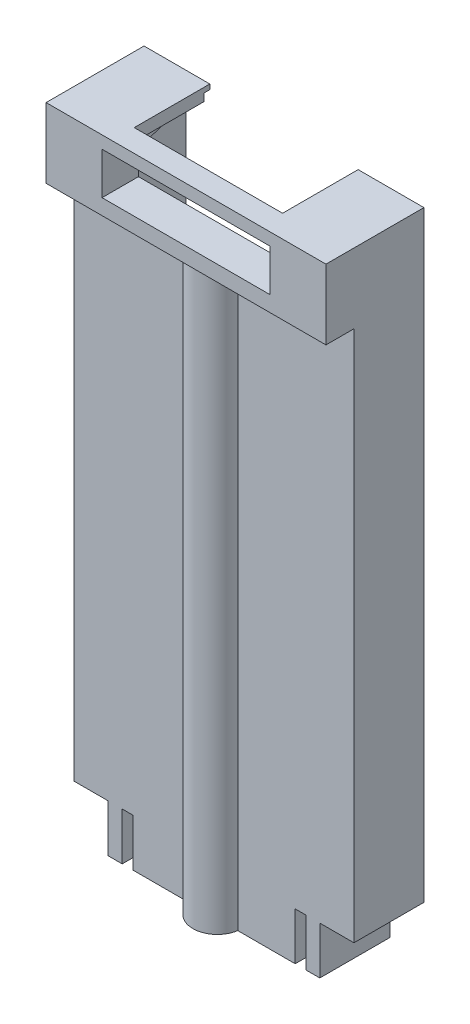
SolidWorks part; units mm, degrees
ref_plane "Front Plane" through (0, 0, 0) normal (0, 0, 1) x (1, 0, 0)
ref_plane "Top Plane" through (0, 0, 0) normal (0, 1, 0) x (1, 0, 0)
ref_plane "Right Plane" through (0, 0, 0) normal (1, 0, 0) x (0, 0, -1)
sketch "Sketch2" plane through (0, 0, 0) normal (0, 0, 1) x (1, 0, 0)
  line L1 (0, 0) -> (20, 0)
  line L2 (0, 0) -> (0, 43)
  line L3 (0, 43) -> (20, 43)
  line L4 (20, 0) -> (20, 43)
  dimension "D1" = 20
  dimension "D2" = 43
extrude "Boss-Extrude1" add sketch "Sketch2" along normal blind 5
sketch "Sketch3" plane through (0, 0, 5) normal (0, 0, 1) x (1, 0, 0)
  line L0 (20, 0) -> (20, 43) construction
  line L1 (0, 43) -> (20, 43)
  line L2 (0, 43) -> (0, 38)
  line L3 (0, 38) -> (20, 38)
  line L4 (20, 43) -> (20, 38)
  dimension "D1" = 5
extrude "Boss-Extrude2" add sketch "Sketch3" along normal blind 2
sketch "Sketch4" plane through (0, 0, 0) normal (0, -1, 0) x (1, 0, 0)
  line L0 (0, 5) -> (20, 5) construction
  line L1 (0, 5) -> (2.44, 5) construction
  line L2 (20, 5) -> (17.56, 5) construction
  line L3 (0, 0) -> (20, 0) construction
  line L4 (2.44, 5) -> (3.44, 5)
  line L5 (2.44, 5) -> (2.44, 0)
  line L6 (2.44, 0) -> (3.44, 0)
  line L7 (3.44, 5) -> (3.44, 0)
  line L8 (20, 5) -> (20, 0) construction
  line L9 (17.56, 5) -> (16.56, 5)
  line L10 (17.56, 5) -> (17.56, 0)
  line L11 (17.56, 0) -> (16.56, 0)
  line L12 (16.56, 5) -> (16.56, 0)
  line L13 (0, 5) -> (0, 0) construction
  dimension "D1" = 1
  dimension "D2" = 1
  dimension "D3" = 2.44
  dimension "D4" = 2.44
extrude "Boss-Extrude4" add sketch "Sketch4" along normal blind 3.4
sketch "Sketch6" plane through (0, 0, 0) normal (0, -1, 0) x (1, 0, 0)
  line L0 (3.44, 5) -> (4.2, 5) construction
  line L1 (3.44, 5) -> (16.56, 5) construction
  line L2 (16.56, 5) -> (15.8, 5) construction
  line L3 (0, 5) -> (20, 5) construction
  line L4 (3.44, 0) -> (16.56, 0) construction
  line L5 (4.2, 5) -> (15.8, 5)
  line L6 (4.2, 5) -> (4.2, 0)
  line L7 (4.2, 0) -> (15.8, 0)
  line L8 (15.8, 5) -> (15.8, 0)
extrude "Boss-Extrude5" add sketch "Sketch6" along normal blind 3.4
sketch "Sketch8" plane through (0, 43, 0) normal (0, 1, 0) x (1, 0, 0)
  line L0 (0, 0) -> (3.8, 0) construction
  line L1 (20, 0) -> (0, 0) construction
  line L2 (20, 0) -> (16.2, 0) construction
  line L4 (3.8, 0) -> (16.2, 0)
  line L5 (3.8, 0) -> (3.8, -3.6)
  line L6 (3.8, -3.6) -> (16.2, -3.6)
  line L7 (16.2, 0) -> (16.2, -3.6)
  dimension "D1" = 3.8
  dimension "D2" = 3.6
extrude "Cut-Extrude1" cut sketch "Sketch8" against normal through all
sketch "Sketch9" plane through (0, -3.4, 0) normal (0, -1, 0) x (1, 0, 0)
  line L0 (20, 5) -> (11.4485, 5) construction
  line L1 (15.8, 5) -> (4.2, 5) construction
  line L2 (0, 5) -> (8.5, 5) construction
  line L3 (8.5, 5) -> (11.4485, 5)
  arc A0 (8.5, 5) -> (11.4485, 5) centre (9.9743, 4.7233) cw
  dimension "D1" = 1.5
extrude "Boss-Extrude6" add sketch "Sketch9" against normal up to surface (41.4 mm away) up to face at (10, 38, 6)
sketch "Sketch10" plane through (0, -3.4, 0) normal (0, -1, 0) x (1, 0, 0)
  circle A0 centre (9.9743, 4.7233) radius 1.2
  dimension "D1" = 2.4
extrude "Cut-Extrude2" cut sketch "Sketch10" against normal up to surface (41.4 mm away) up to face at (9.9914, 38, 5.8706)
sketch "Sketch12" plane through (0, -3.4, 0) normal (0, -1, 0) x (1, 0, 0)
  line L0 (8.7743, 4.7233) -> (8.7743, 3.6)
  line L1 (9.5522, 3.6) -> (4.2, 3.6) construction
  line L2 (11.1743, 4.7233) -> (11.1743, 3.6)
  line L3 (15.8, 3.6) -> (10.3963, 3.6) construction
  line L4 (11.1743, 3.6) -> (8.7743, 3.6)
  line L5 (8.7743, 4.7233) -> (11.1743, 4.7233)
  arc A0 (10.3963, 3.6) -> (9.5522, 3.6) centre (9.9743, 4.7233) ccw construction
  arc A1 (10.3963, 3.6) -> (9.5522, 3.6) centre (9.9743, 4.7233) ccw construction
extrude "Cut-Extrude3" cut sketch "Sketch12" against normal up to surface (41.4 mm away) up to face at (9.9914, 38, 5.8706)
sketch "Sketch14" plane through (0, 0, 7) normal (0, 0, 1) x (1, 0, 0)
  line L0 (0, 43) -> (4, 43) construction
  line L1 (20, 43) -> (0, 43) construction
  line L2 (20, 43) -> (16, 43) construction
  line L3 (4, 43) -> (4, 42.1129) construction
  line L4 (16, 43) -> (16, 42.1129) construction
  line L6 (4, 42.1129) -> (16, 42.1129)
  line L7 (4, 42.1129) -> (4, 39.1129)
  line L8 (4, 39.1129) -> (16, 39.1129)
  line L9 (16, 42.1129) -> (16, 39.1129)
  dimension "D1" = 4
  dimension "D2" = 3
extrude "Cut-Extrude5" cut sketch "Sketch14" against normal up to surface (3.4 mm away) up to face at (9.9914, 12.3667, 3.6)
sketch "Sketch15" plane through (3.8, 0, 0) normal (1, 0, 0) x (0, 0, -1)
  line L1 (-3.6, 43) -> (0, 43)
  line L2 (-3.6, 43) -> (-3.6, 0)
  line L3 (-3.6, 0) -> (0, 0)
  line L4 (0, 43) -> (0, 0)
extrude "Cut-Extrude6" cut sketch "Sketch15" against normal blind 0.8
sketch "Sketch16" plane through (16.2, 0, 0) normal (-1, 0, 0) x (0, 0, 1)
  line L1 (3.6, 43) -> (0, 43)
  line L2 (3.6, 43) -> (3.6, 0)
  line L3 (3.6, 0) -> (0, 0)
  line L4 (0, 43) -> (0, 0)
extrude "Cut-Extrude7" cut sketch "Sketch16" against normal blind 0.8
sketch "Sketch17" plane through (0, 0, 3.6) normal (0, 0, -1) x (-1, 0, 0)
  line L0 (-3, 43) -> (-3, 0) construction
  line L1 (-17, 43) -> (-3, 43)
  line L2 (-17, 43) -> (-17, -0.0362)
  line L3 (-17, -0.0362) -> (-3, -0.0362)
  line L4 (-3, 43) -> (-3, -0.0362)
extrude "Cut-Extrude8" cut sketch "Sketch17" against normal blind 0.8
sketch "Sketch18" plane through (17, 0, 0) normal (-1, 0, 0) x (0, 0, 1)
  line L0 (0, 43) -> (0, 0) construction
  line L1 (4.4, 43) -> (0, 43)
  line L2 (4.4, 43) -> (4.4, 42.3)
  line L3 (4.4, 42.3) -> (0, 42.3)
  line L4 (0, 43) -> (0, 42.3)
  dimension "D1" = 0.7
extrude "Boss-Extrude7" add sketch "Sketch18" along normal blind 0.7
sketch "Sketch19" plane through (3, 0, 0) normal (1, 0, 0) x (0, 0, -1)
  line L0 (0, 0) -> (0, 43) construction
  line L1 (-4.4, 43) -> (0, 43)
  line L2 (-4.4, 43) -> (-4.4, 42.3)
  line L3 (-4.4, 42.3) -> (0, 42.3)
  line L4 (0, 43) -> (0, 42.3)
  dimension "D1" = 0.7
extrude "Boss-Extrude8" add sketch "Sketch19" along normal blind 0.7
sketch "Sketch21" plane through (3.7, 0, 0) normal (1, 0, 0) x (0, 0, -1)
  line L1 (-4.4, 43) -> (0, 43)
  line L2 (-4.4, 43) -> (-4.4, 42.3)
  line L3 (-4.4, 42.3) -> (0, 42.3)
  line L4 (0, 43) -> (0, 42.3)
extrude "Boss-Extrude10" add sketch "Sketch21" along normal blind 1
sketch "Sketch22" plane through (16.3, 0, 0) normal (-1, 0, 0) x (0, 0, 1)
  line L0 (0, 42.3) -> (4.4, 42.3) construction
  line L1 (4.4, 43) -> (0, 43)
  line L2 (4.4, 43) -> (4.4, 42.3)
  line L3 (4.4, 42.3) -> (0, 42.3)
  line L4 (0, 43) -> (0, 42.3)
extrude "Boss-Extrude11" add sketch "Sketch22" along normal blind 1
sketch "Sketch23" plane through (0, 42.3, 0) normal (0, -1, 0) x (1, 0, 0)
  line L1 (17, 4.4) -> (15.3, 4.4)
  line L2 (17, 4.4) -> (17, 0)
  line L3 (17, 0) -> (15.3, 0)
  line L4 (15.3, 4.4) -> (15.3, 0)
  line L5 (3, 4.4) -> (4.7, 4.4)
  line L6 (3, 4.4) -> (3, 0)
  line L7 (3, 0) -> (4.7, 0)
  line L8 (4.7, 4.4) -> (4.7, 0)
extrude "Boss-Extrude12" add sketch "Sketch23" along normal blind 2
sketch "Sketch24" plane through (15.3, 0, 0) normal (-1, 0, 0) x (0, 0, 1)
  line L0 (0, 40.3) -> (0, 41.65)
  line L1 (0, 43) -> (0, 40.3) construction
  line L2 (0, 41.65) -> (4.4, 40.3)
  line L3 (4.4, 40.3) -> (0, 40.3) construction
  line L4 (4.4, 40.3) -> (0, 40.3)
extrude "Cut-Extrude9" cut sketch "Sketch24" against normal up to surface (1.7 mm away) up to face at (17, 13.4213, 2.6667)
sketch "Sketch25" plane through (15.3, 0, 0) normal (-1, 0, 0) x (0, 0, 1)
  line L0 (0, 41.65) -> (0, 41.8905)
  line L1 (0, 43) -> (0, 41.65) construction
  line L6 (0, 41.65) -> (4.4, 40.3)
  line L7 (4.4, 40.3) -> (4.4, 40.5671)
  line L8 (4.4, 40.3) -> (4.4, 42.1129) construction
  line L9 (4.4, 40.5671) -> (0, 41.9631)
  line L10 (0, 41.9631) -> (0, 41.8905)
extrude "Cut-Extrude10" cut sketch "Sketch25" against normal up to surface (1.7 mm away) up to face at (17, 13.6463, 2.6667)
sketch "Sketch26" plane through (4.7, 0, 0) normal (1, 0, 0) x (0, 0, -1)
  line L0 (0, 40.3) -> (0, 41.65)
  line L1 (0, 40.3) -> (0, 43) construction
  line L2 (0, 41.65) -> (-4.4, 40.3)
  line L3 (-4.4, 40.3) -> (0, 40.3)
extrude "Cut-Extrude11" cut sketch "Sketch26" against normal up to surface (1.7 mm away) up to face at (3, 13.4213, 2.6667)
sketch "Sketch27" plane through (4.7, 0, 0) normal (1, 0, 0) x (0, 0, -1)
  line L0 (-4.4, 40.3) -> (-4.4, 40.64)
  line L1 (-4.4, 40.3) -> (-4.4, 42.1129) construction
  line L5 (0, 41.65) -> (-4.4, 40.3)
  line L6 (-4.4, 40.64) -> (0, 41.99)
  line L7 (0, 41.65) -> (0, 43) construction
  line L8 (0, 41.99) -> (0, 41.65)
  dimension "D1" = 0.34
extrude "Cut-Extrude12" cut sketch "Sketch27" against normal up to surface (1.7 mm away) up to face at (3, 13.6463, 2.6667)
sketch "Sketch32" plane through (4.7, 0, 0) normal (1, 0, 0) x (0, 0, -1)
  line L0 (-4.4, 40.64) -> (-4.4, 40.8906)
  line L1 (-4.4, 40.64) -> (-4.4, 42.1129) construction
  line L2 (-4.4, 40.8906) -> (0, 42.24)
  line L3 (0, 41.99) -> (0, 43) construction
  line L4 (0, 42.24) -> (0, 41.99)
  line L5 (0, 41.99) -> (-4.4, 40.64) construction
  line L6 (0, 41.99) -> (-4.4, 40.64)
  dimension "D1" = 0.25
  dimension "D2" = 0.2506
extrude "Cut-Extrude17" cut sketch "Sketch32" against normal up to surface (1.7 mm away)
sketch "Sketch33" plane through (15.3, 0, 0) normal (-1, 0, 0) x (0, 0, 1)
  line L0 (4.4, 40.5671) -> (4.4, 40.8171)
  line L1 (4.4, 40.5671) -> (4.4, 42.1129) construction
  line L2 (4.4, 40.8171) -> (0, 42.2131)
  line L3 (0, 43) -> (0, 41.9631) construction
  line L4 (0, 42.2131) -> (0, 41.9631)
  line L5 (4.4, 40.5671) -> (0, 41.9631) construction
  line L6 (0, 41.9631) -> (4.4, 40.5671)
  dimension "D1" = 0.25
extrude "Cut-Extrude18" cut sketch "Sketch33" against normal up to surface (1.7 mm away) up to face at (17, 13.743, 2.6667)
sketch "Sketch34" plane through (0, -3.4, 0) normal (0, -1, 0) x (1, 0, 0)
  line L0 (8.5, 5) -> (8.25, 5)
  line L1 (0, 5) -> (8.5, 5) construction
  line L2 (11.4485, 5) -> (11.6985, 5)
  line L3 (11.4485, 5) -> (20, 5) construction
  arc A0 (8.25, 5) -> (11.6985, 5) centre (9.9743, 4.7365) cw
  arc A1 (8.5, 5) -> (11.4485, 5) centre (9.9743, 4.7233) cw
  dimension "D1" = 0.25
  dimension "D2" = 0.25
extrude "Boss-Extrude13" add sketch "Sketch34" against normal up to surface (41.4 mm away) up to face at (9.9914, 38, 5.8706)
sketch "Sketch35" plane through (0, 0, 4.4) normal (0, 0, 1) x (1, 0, 0)
  line L0 (16, 40.8171) -> (15.3, 40.8171) construction
  line L1 (16, 42.1129) -> (15.3, 42.1129)
  line L2 (16, 42.1129) -> (16, 40.8171)
  line L3 (16, 40.8171) -> (15.3, 40.8171)
  line L4 (15.3, 42.1129) -> (15.3, 40.8171)
  line L5 (15.3, 40.8171) -> (15.3, 42.1129) construction
  line L7 (4, 42.1129) -> (4.7, 42.1129)
  line L8 (4, 42.1129) -> (4, 40.8906)
  line L9 (4, 40.8906) -> (4.7, 40.8906)
  line L10 (4.7, 42.1129) -> (4.7, 40.8906)
extrude "Cut-Extrude19" cut sketch "Sketch35" against normal blind 10
sketch "Sketch36" plane through (15.3, 0, 0) normal (-1, 0, 0) x (0, 0, 1)
  line L0 (0, 42.2131) -> (0.316, 42.1129)
  line L1 (0.316, 42.1129) -> (0.6638, 42.1129)
  line L2 (0.316, 42.1129) -> (4.4, 42.1129) construction
  line L3 (0.6638, 42.1129) -> (0.6638, 42.4574)
  line L4 (0.6638, 42.4574) -> (0, 42.4574)
  line L5 (0, 43) -> (0, 42.2131) construction
  line L6 (0, 42.4574) -> (0, 42.2131)
extrude "Cut-Extrude20" cut sketch "Sketch36" against normal up to surface (0.7 mm away) up to face at (16, 40.6537, 4.6232)
sketch "Sketch37" plane through (4.7, 0, 0) normal (1, 0, 0) x (0, 0, -1)
  line L0 (0, 42.24) -> (-0.4145, 42.1129)
  line L1 (-0.4145, 42.1129) -> (-0.4145, 42.6466)
  line L2 (-0.4145, 42.6466) -> (0, 42.6466)
  line L3 (0, 42.24) -> (0, 43) construction
  line L4 (0, 42.6466) -> (0, 42.24)
extrude "Cut-Extrude21" cut sketch "Sketch37" against normal up to surface (0.7 mm away) up to face at (4, 40.6684, 4.6429)
sketch "Sketch38" plane through (0, 0, 4.4) normal (0, 0, -1) x (-1, 0, 0)
  line L1 (-15.3, 43) -> (-4.7, 43)
  line L2 (-15.3, 43) -> (-15.3, 42.1129)
  line L3 (-15.3, 42.1129) -> (-4.7, 42.1129)
  line L4 (-4.7, 43) -> (-4.7, 42.1129)
extrude "Cut-Extrude22" cut sketch "Sketch38" against normal blind 1
